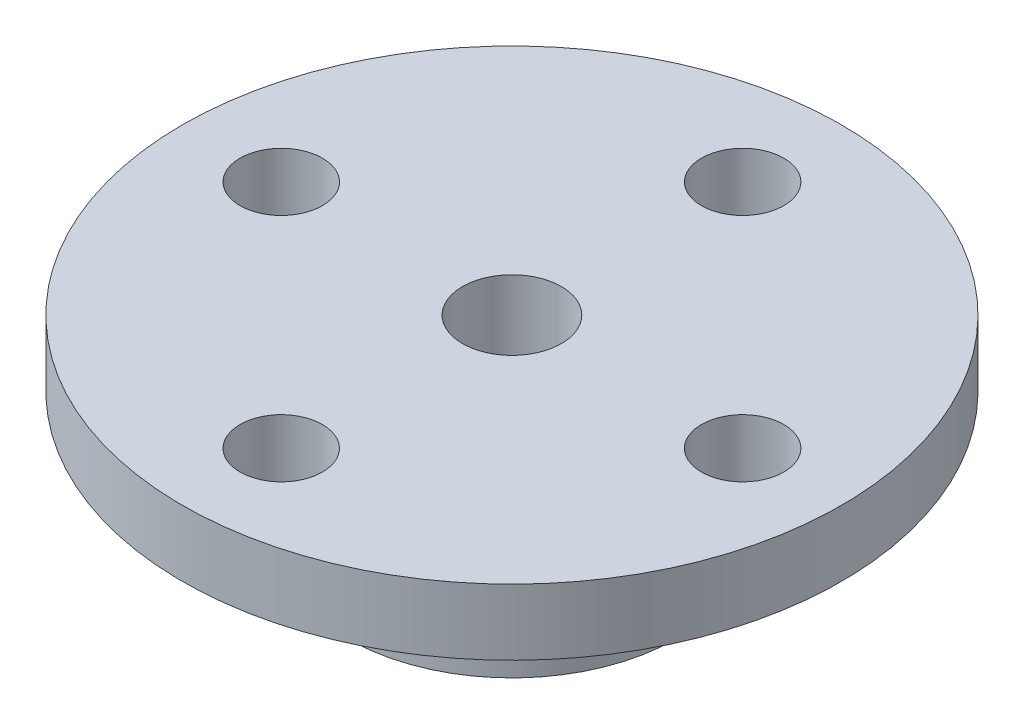
SolidWorks part; units mm, degrees
material "1060 合金"
ref_plane "前视" through (0, 0, 0) normal (0, 0, 1) x (1, 0, 0)
ref_plane "上视" through (0, 0, 0) normal (0, 1, 0) x (1, 0, 0)
ref_plane "右视" through (0, 0, 0) normal (1, 0, 0) x (0, 0, -1)
sketch "草图1" plane through (0, 0, 0) normal (0, 0, 1) x (1, 0, 0)
  line L0 (0, 0) -> (0, -9.9107) construction
  line L1 (10, 0) -> (1.5, 0)
  line L2 (1.5, 0) -> (1.5, -3)
  line L3 (1.5, -3) -> (3, -3)
  line L4 (3, -3) -> (3, -6)
  line L6 (10, 0) -> (10, -2)
  line L7 (10, -2) -> (5, -2)
  line L8 (5, -2) -> (5, -6)
  line L9 (5, -6) -> (3, -6)
  dimension "D1" = 3
  dimension "D2" = 20
  dimension "D3" = 2
  dimension "D4" = 6
  dimension "D5" = 6
  dimension "D6" = 10
  dimension "D7" = 3
revolve "旋转1" add sketch "草图1" angle 360 about L0
hole_wizard "M3 螺纹孔1" positions "草图3" profile "草图2" tap size "M3" standard "GB" end condition through all
sketch "草图3" plane through (0, -2, 0) normal (0, -1, 0) x (-1, 0, 0)
  circle A0 centre (0, 0) radius 7 construction
  point P0 (7, 0)
  point P2 (0, -7)
  point P4 (-7, 0)
  point P6 (0, 7)
  dimension "D1" = 14
sketch "草图2" plane through (-7, -2, 0) normal (1, 0, 0) x (0, 0, -1)
  line L0 (0, 0) -> (0, 2)
  line L1 (0, 2) -> (1.25, 2)
  line L2 (1.25, 2) -> (1.25, 0)
  line L5 (1.25, 0) -> (0, 0)
  line L11 (0, -6.35) -> (0, 107.95) construction
  dimension "通孔螺纹孔钻头直径" = 2.5
  dimension "通孔螺纹孔钻头深度" = 2
cosmetic thread "孔螺蚊线1" parameters "D2"=3
cosmetic thread "孔螺蚊线2" parameters "D2"=3
cosmetic thread "孔螺蚊线3" parameters "D2"=3
cosmetic thread "孔螺蚊线4" parameters "D2"=3
sketch "草图4" plane through (0, 0, 0) normal (0, 1, 0) x (1, 0, 0)
  line L0 (-10, 0) -> (10, 0) construction
  circle A0 centre (0, 0) radius 10 construction
